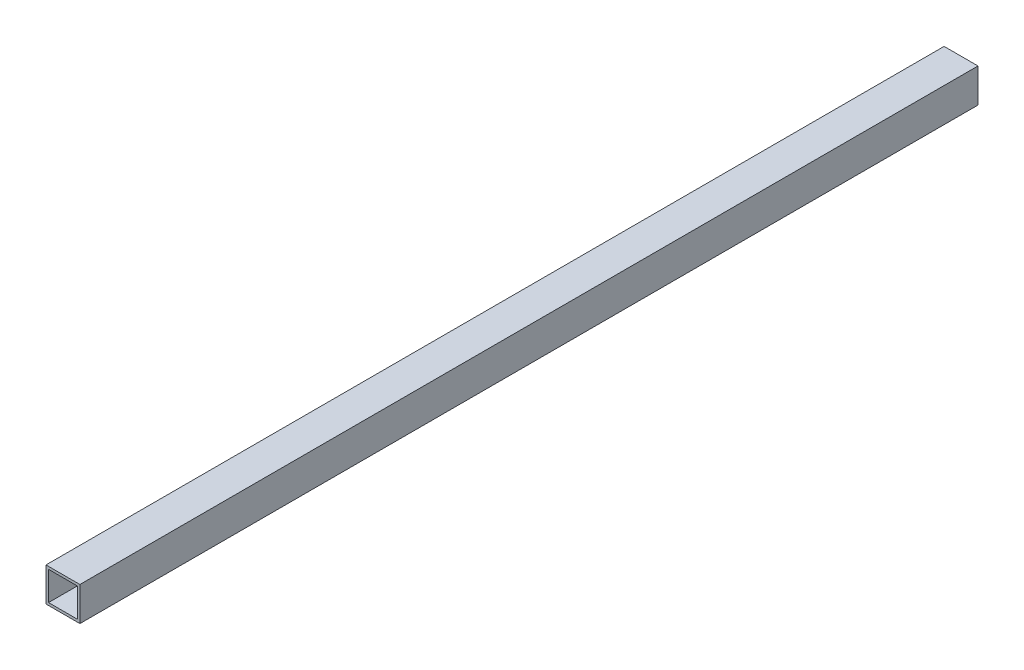
SolidWorks part; units mm, degrees
ref_plane "正面" through (0, 0, 0) normal (0, 0, 1) x (1, 0, 0)
ref_plane "平面" through (0, 0, 0) normal (0, 1, 0) x (1, 0, 0)
ref_plane "右側面" through (0, 0, 0) normal (1, 0, 0) x (0, 0, -1)
sketch "ｽｹｯﾁ2" plane through (0, 0, 0) normal (0, 0, 1) x (1, 0, 0)
  line L0 (-8.5, 8.5) -> (-8.5, -8.5)
  line L1 (-10, 10) -> (10, 10)
  line L2 (-10, 10) -> (-10, -10)
  line L3 (-10, -10) -> (10, -10)
  line L4 (10, 10) -> (10, -10)
  line L5 (-10, 10) -> (10, -10) construction
  line L6 (-10, -10) -> (10, 10) construction
  line L7 (-8.5, -8.5) -> (8.5, -8.5)
  line L8 (8.5, 8.5) -> (8.5, -8.5)
  line L9 (-8.5, 8.5) -> (8.5, 8.5)
  point P0 (0, 0)
  dimension "D1" = 20
  dimension "D2" = 20
  dimension "D3" = 1.5
extrude "ﾎﾞｽ - 押し出し1" add sketch "ｽｹｯﾁ2" along normal blind 530
